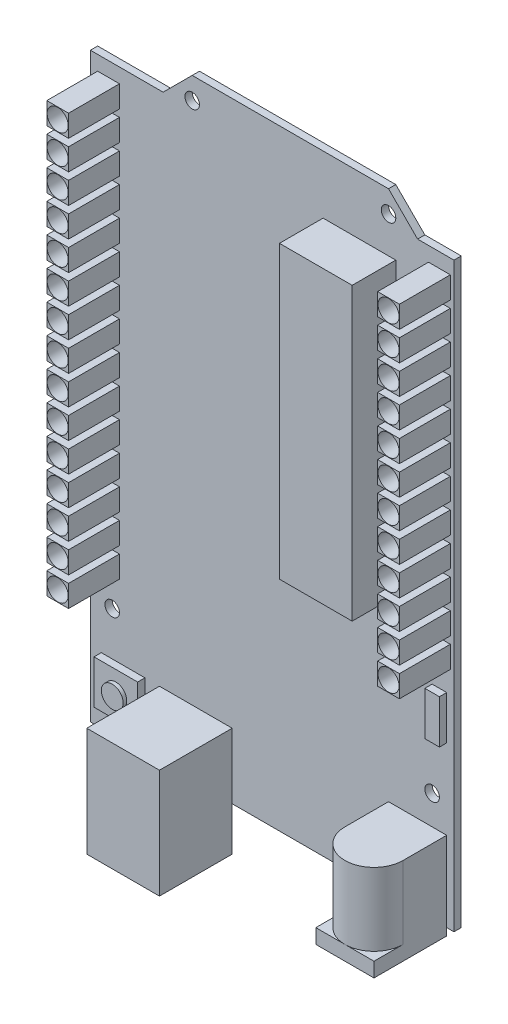
SolidWorks part; units mm, degrees
ref_plane "Front Plane" through (0, 0, 0) normal (0, 0, 1) x (1, 0, 0)
ref_plane "Top Plane" through (0, 0, 0) normal (0, 1, 0) x (1, 0, 0)
ref_plane "Right Plane" through (0, 0, 0) normal (1, 0, 0) x (0, 0, -1)
sketch "Sketch1" plane through (0, 0, 0) normal (0, 0, 1) x (1, 0, 0)
  line L0 (20, 40) -> (16, 44)
  line L1 (-25, -40) -> (25, -40)
  line L2 (-25, -40) -> (-25, 40)
  line L3 (-25, 40) -> (25, 40)
  line L4 (25, -40) -> (25, 40)
  line L5 (-25, -40) -> (25, 40) construction
  line L6 (-25, 40) -> (25, -40) construction
  line L7 (16, 44) -> (-11, 44)
  line L8 (-11, 44) -> (-15, 40)
  point P0 (0, 0)
  point P9 (0, 0)
  point P11 (9.523, 44.243)
  point P12 (19.0193, 40)
  dimension "D1" = 80
  dimension "D2" = 50
  dimension "D3" = 10
  dimension "D4" = 5
  dimension "D5" = 4
  dimension "D6" = 4
  dimension "D7" = 4
extrude "Boss-Extrude1" add sketch "Sketch1" along normal blind 1 contours L7 L8 L3 L0 | L1 L4 L3 L2
sketch "Sketch2" plane through (0, 0, 1) normal (0, 0, 1) x (1, 0, 0)
  line L0 (16, 44) -> (-11, 44) construction
  line L1 (25, -40) -> (25, 40) construction
  line L2 (-25, -40) -> (-25, 40) construction
  line L3 (-25, -40) -> (25, -40) construction
  circle A0 centre (-11, 41) radius 1
  circle A1 centre (16, 41) radius 1
  circle A2 centre (-22, -25) radius 1
  circle A3 centre (22, -25) radius 1
  point P13 (0, 0)
  dimension "D1" = 2
  dimension "D3" = 2
  dimension "D5" = 2
  dimension "D6" = 2
  dimension "D2" = 3
  dimension "D4" = 3
  dimension "D7" = 3
  dimension "D8" = 3
  dimension "D9" = 15
extrude "Cut-Extrude1" cut sketch "Sketch2" against normal blind 1
sketch "Sketch3" plane through (0, 0, 1) normal (0, 0, 1) x (1, 0, 0)
  line L0 (25, -40) -> (25, 40) construction
  line L1 (24.5, 38) -> (21.5, 38)
  line L2 (24.5, 38) -> (24.5, 35)
  line L3 (24.5, 35) -> (21.5, 35)
  line L4 (21.5, 38) -> (21.5, 35)
  line L5 (24.5, 38) -> (21.5, 35) construction
  line L6 (24.5, 35) -> (21.5, 38) construction
  line L7 (20, 40) -> (25, 40) construction
  circle A0 centre (23, 36.5) radius 1.45
  point P0 (23, 36.5)
  dimension "D5" = 2.9
  dimension "D1" = 2
  dimension "D2" = 3
  dimension "D3" = 3
  dimension "D4" = 2
extrude "Boss-Extrude2" add sketch "Sketch3" along normal blind 7
pattern_linear "LPattern1" count 12 spacing 4 along (0, -1, 0) of "Boss-Extrude2"
sketch "Sketch4" plane through (0, 0, 1) normal (0, 0, 1) x (1, 0, 0)
  line L0 (25, -40) -> (25, 40) construction
  line L1 (24, -12) -> (22, -12)
  line L2 (24, -12) -> (24, -18)
  line L3 (24, -18) -> (22, -18)
  line L4 (22, -12) -> (22, -18)
  line L5 (24, -12) -> (22, -18) construction
  line L6 (24, -18) -> (22, -12) construction
  circle A1 centre (22, -25) radius 1 construction
  point P0 (23, -15)
  point P5 (0, 0)
  dimension "D1" = 6
  dimension "D2" = 2
  dimension "D3" = 7
  dimension "D4" = 1
extrude "Boss-Extrude3" add sketch "Sketch4" along normal blind 1
sketch "Sketch5" plane through (0, 0, 1) normal (0, 0, 1) x (1, 0, 0)
  line L0 (25, -40) -> (25, 40) construction
  line L1 (17, 36) -> (7, 36)
  line L2 (17, 36) -> (17, -4)
  line L3 (17, -4) -> (7, -4)
  line L4 (7, 36) -> (7, -4)
  line L5 (20, 40) -> (25, 40) construction
  point P6 (25, 0)
  point P7 (12, 36)
  dimension "D1" = 10
  dimension "D2" = 8
  dimension "D3" = 40
  dimension "D4" = 4
extrude "Boss-Extrude4" add sketch "Sketch5" along normal blind 6
sketch "Sketch6" plane through (0, 0, 1) normal (0, 0, 1) x (1, 0, 0)
  line L0 (-21, 38) -> (-24, 38)
  line L1 (-21, 38) -> (-21, 35)
  line L2 (-21, 35) -> (-24, 35)
  line L3 (-24, 38) -> (-24, 35)
  line L4 (-21, 38) -> (-24, 35) construction
  line L5 (-21, 35) -> (-24, 38) construction
  line L6 (-25, -40) -> (-25, 40) construction
  line L7 (-25, 40) -> (-15, 40) construction
  circle A0 centre (-22.5, 36.5) radius 1.45
  point P0 (-22.5, 36.5)
  dimension "D3" = 2.9
  dimension "D1" = 3
  dimension "D2" = 3
  dimension "D4" = 1
  dimension "D5" = 2
extrude "Boss-Extrude5" add sketch "Sketch6" along normal blind 7
pattern_linear "LPattern3" count 15 spacing 4 along (0, -1, 0) of "Boss-Extrude5"
sketch "Sketch7" plane through (0, 0, 1) normal (0, 0, 1) x (1, 0, 0)
  line L0 (-25, -40) -> (25, -40) construction
  line L1 (-23.5, -37) -> (-17.5, -37)
  line L2 (-23.5, -37) -> (-23.5, -31)
  line L3 (-23.5, -31) -> (-17.5, -31)
  line L4 (-17.5, -37) -> (-17.5, -31)
  line L5 (-25, -40) -> (-25, 40) construction
  dimension "D1" = 6
  dimension "D2" = 3
  dimension "D3" = 1.5
extrude "Boss-Extrude6" add sketch "Sketch7" along normal blind 1
sketch "Sketch8" plane through (0, 0, 2) normal (0, 0, 1) x (1, 0, 0)
  line L0 (-17.5, -37) -> (-17.5, -31) construction
  line L1 (-23.5, -37) -> (-17.5, -37) construction
  circle A0 centre (-20.5, -34) radius 1.5
  point P2 (0, 0)
  point P5 (-17.5, -34)
  point P8 (-20.5, -37)
  dimension "D1" = 3
extrude "Boss-Extrude7" add sketch "Sketch8" along normal blind 0.5
sketch "Sketch9" plane through (0, 0, 1) normal (0, 0, 1) x (1, 0, 0)
  line L1 (-15.5, -31) -> (-5.5, -31)
  line L2 (-15.5, -31) -> (-15.5, -46)
  line L3 (-15.5, -46) -> (-5.5, -46)
  line L4 (-5.5, -31) -> (-5.5, -46)
  line L5 (-25, -40) -> (25, -40) construction
  line L6 (-17.5, -37) -> (-17.5, -31) construction
  point P4 (0, 0)
  dimension "D1" = 10
  dimension "D2" = 15
  dimension "D3" = 9
  dimension "D4" = 2
extrude "Boss-Extrude8" add sketch "Sketch9" along normal blind 10
sketch "Sketch10" plane through (0, -46, 0) normal (0, -1, 0) x (1, 0, 0)
  line L0 (-14.75, 1.75) -> (-6.25, 1.75)
  line L1 (-6.25, 1.75) -> (-6.25, 7.75)
  line L2 (-6.25, 7.75) -> (-8.25, 9.75)
  line L3 (-8.25, 9.75) -> (-12.75, 9.75)
  line L4 (-12.75, 9.75) -> (-14.75, 7.75)
  line L5 (-14.75, 7.75) -> (-14.75, 1.75)
  line L6 (-15.5, 11) -> (-15.5, 1) construction
  line L8 (-15.5, 1) -> (-5.5, 1) construction
  line L12 (-12.4988, 3.75) -> (-8.5012, 3.75)
  line L13 (-12.4988, 3.75) -> (-12.4988, 5.75)
  line L14 (-12.4988, 5.75) -> (-8.5012, 5.75)
  line L15 (-8.5012, 3.75) -> (-8.5012, 5.75)
  point P14 (-10.5, 3.75)
  point P15 (-10.5, 1.75)
  point P16 (-8.5012, 4.75)
  point P17 (-6.25, 4.75)
  dimension "D1" = 8.5
  dimension "D2" = 0.75
  dimension "D3" = 2
  dimension "D4" = 2
  dimension "D5" = 8
  dimension "D6" = 0.75
  dimension "D7" = 2
  dimension "D8" = 2
  dimension "D9" = 3.9976
extrude "Cut-Extrude2" cut sketch "Sketch10" against normal blind 10 contours L4 L5 L0 L1 L2 L3 L15 L12 L13 L14
sketch "Sketch11" plane through (0, 0, 1) normal (0, 0, 1) x (1, 0, 0)
  line L0 (25, -40) -> (25, 40) construction
  line L1 (16, -39) -> (24, -39)
  line L2 (16, -39) -> (16, -41)
  line L3 (16, -41) -> (24, -41)
  line L4 (24, -39) -> (24, -41)
  line L6 (-5.5, -40) -> (25, -40) construction
  dimension "D1" = 1
  dimension "D2" = 2
  dimension "D3" = 8
  dimension "D4" = 1
extrude "Boss-Extrude9" add sketch "Sketch11" along normal blind 10
sketch "Sketch12" plane through (0, -39, 0) normal (0, 1, 0) x (1, 0, 0)
  line L0 (16, -1) -> (24, -1)
  line L1 (24, -1) -> (24, -7)
  line L2 (24, -11) -> (24, -1) construction
  line L3 (16, -1) -> (16, -7)
  line L4 (16, -11) -> (16, -1) construction
  line L5 (24, -11) -> (16, -11) construction
  arc A0 (16, -7) -> (24, -7) centre (20, -7) ccw
  point P14 (0, 0)
  point P15 (0, 0)
extrude "Boss-Extrude10" add sketch "Sketch12" along normal blind 10
sketch "Sketch13" plane through (0, -41, 0) normal (0, -1, 0) x (1, 0, 0)
  line L1 (16, 11) -> (24, 11) construction
  circle A0 centre (20, 7) radius 3
  circle A1 centre (20, 7) radius 0.5
  dimension "D1" = 6
  dimension "D3" = 1
  dimension "D2" = 4
extrude "Cut-Extrude3" cut sketch "Sketch13" against normal blind 10
